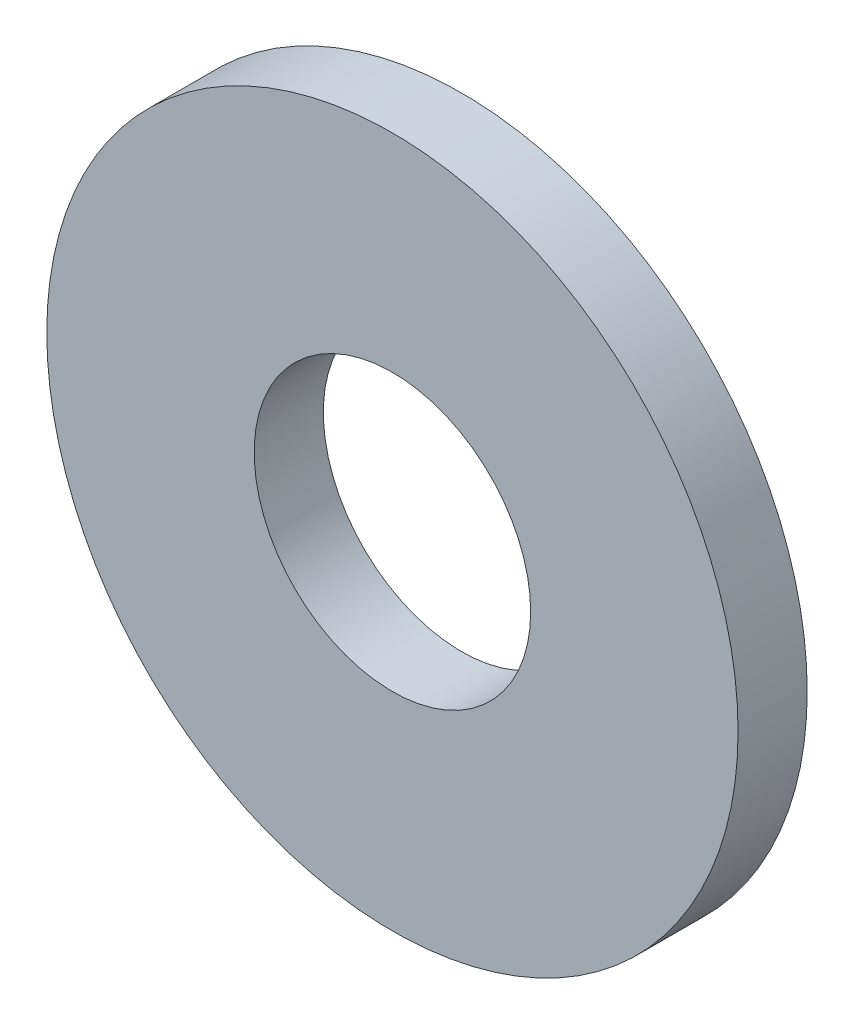
SolidWorks part; units mm, degrees
material "PTFE (general)"
ref_plane "Front" through (0, 0, 0) normal (0, 0, 1) x (1, 0, 0)
ref_plane "Top" through (0, 0, 0) normal (0, 1, 0) x (1, 0, 0)
ref_plane "Side" through (0, 0, 0) normal (1, 0, 0) x (0, 0, -1)
sketch "Sketch1" plane through (0, 0, 0) normal (0, 0, 1) x (1, 0, 0)
  circle A0 centre (0, 0) radius 5
  circle A1 centre (0, 0) radius 2
  dimension "D1" = 10
  dimension "D2" = 4
extrude "Boss-Extrude1" add sketch "Sketch1" along normal blind 1
